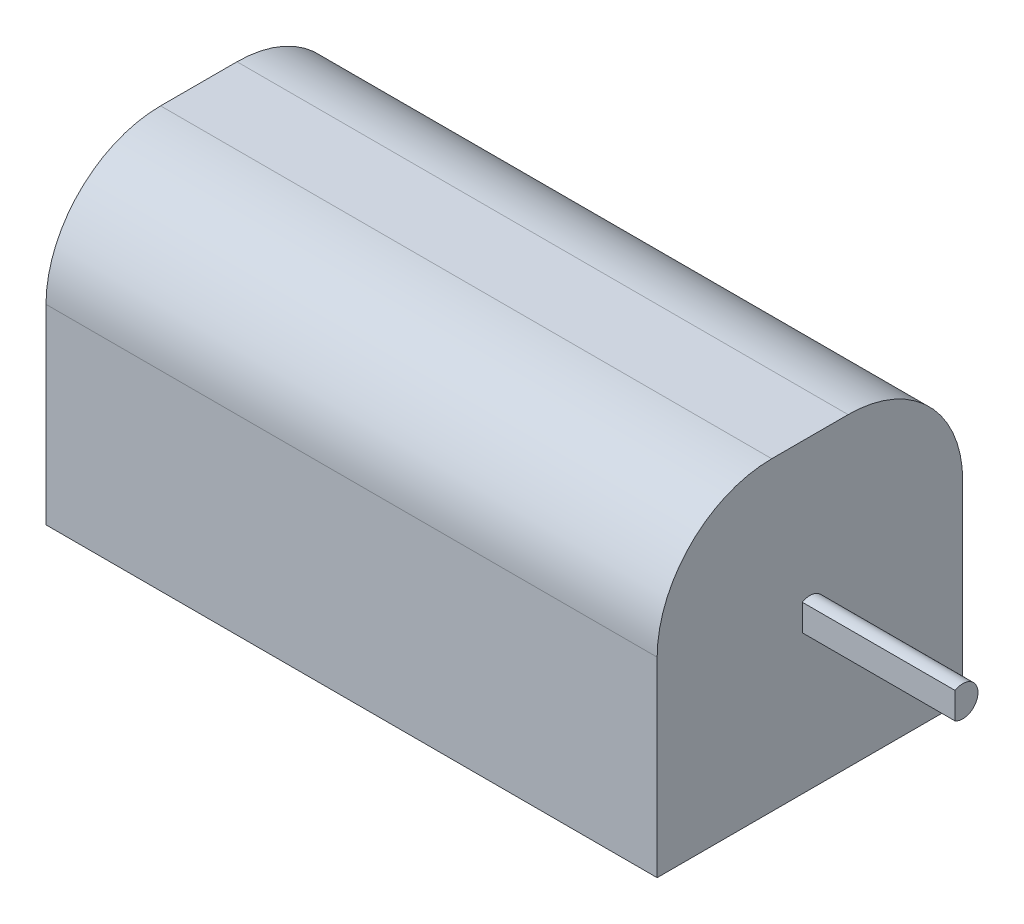
SolidWorks part; units mm, degrees
ref_plane "Front Plane" through (0, 0, 0) normal (0, 0, 1) x (1, 0, 0)
ref_plane "Top Plane" through (0, 0, 0) normal (0, 1, 0) x (1, 0, 0)
ref_plane "Right Plane" through (0, 0, 0) normal (1, 0, 0) x (0, 0, -1)
sketch "Sketch1" plane through (0, 0, 0) normal (0, 1, 0) x (1, 0, 0)
  line L1 (-40, -20) -> (40, -20)
  line L2 (-40, -20) -> (-40, 20)
  line L3 (-40, 20) -> (40, 20)
  line L4 (40, -20) -> (40, 20)
  line L5 (-40, -20) -> (40, 20) construction
  line L6 (-40, 20) -> (40, -20) construction
  point P0 (0, 0)
  dimension "D1" = 80
  dimension "D2" = 40
extrude "Boss-Extrude1" add sketch "Sketch1" along normal mid plane 40
sketch "Sketch4" plane through (0, 0, 0) normal (1, 0, 0) x (0, 0, -1)
  line L0 (-1, 1.7321) -> (-1, -1.7321)
  circle A0 centre (0, 0) radius 2
  point P5 (-1.8, -1.7349)
  dimension "D1" = 4
  dimension "D2" = 1
extrude "Boss-Extrude2" add sketch "Sketch4" along normal blind 20 from surface at 40 contours L0 A0
fillet "Fillet1" radius 15 2 edges at (0, 20, -20) (0, 20, 20)
